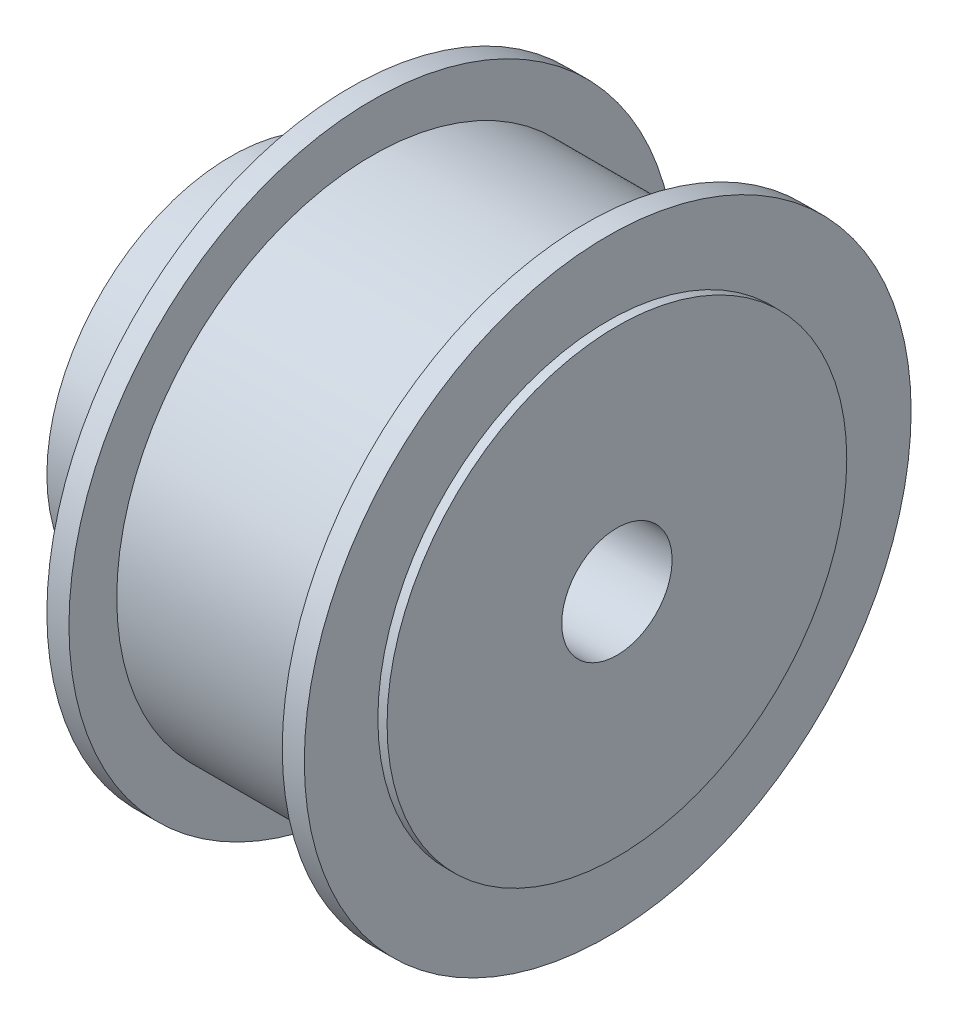
SolidWorks part; units mm, degrees
ref_plane "Alzado" through (0, 0, 0) normal (0, 0, 1) x (1, 0, 0)
ref_plane "Planta" through (0, 0, 0) normal (0, 1, 0) x (1, 0, 0)
ref_plane "Vista lateral" through (0, 0, 0) normal (1, 0, 0) x (0, 0, -1)
sketch "Croquis1" plane through (0, 0, 0) normal (1, 0, 0) x (0, 0, -1)
  circle A0 centre (0, 0) radius 10
  dimension "D1" = 20
extrude "Saliente-Extruir1" add sketch "Croquis1" along normal blind 6
sketch "Croquis2" plane through (6, 0, 0) normal (1, 0, 0) x (0, 0, -1)
  circle A0 centre (0, 0) radius 12.5
  dimension "D1" = 25
extrude "Saliente-Extruir2" add sketch "Croquis2" along normal blind 0.5
sketch "Croquis3" plane through (6.5, 0, 0) normal (1, 0, 0) x (0, 0, -1)
  circle A0 centre (0, 0) radius 16.5
  dimension "D1" = 33
extrude "Saliente-Extruir3" add sketch "Croquis3" along normal blind 1.2
sketch "Croquis4" plane through (7.7, 0, 0) normal (1, 0, 0) x (0, 0, -1)
  circle A0 centre (0, 0) radius 13.9
  dimension "D1" = 27.8
extrude "Saliente-Extruir4" add sketch "Croquis4" along normal blind 11.6
sketch "Croquis5" plane through (19.3, 0, 0) normal (1, 0, 0) x (0, 0, -1)
  circle A0 centre (0, 0) radius 16.5
  dimension "D1" = 33
extrude "Saliente-Extruir5" add sketch "Croquis5" along normal blind 1.2
sketch "Croquis6" plane through (20.5, 0, 0) normal (1, 0, 0) x (0, 0, -1)
  circle A0 centre (0, 0) radius 12.5
  dimension "D1" = 25
extrude "Saliente-Extruir6" add sketch "Croquis6" along normal blind 0.5
sketch "Croquis7" plane through (0, 0, 0) normal (-1, 0, 0) x (0, 0, 1)
  circle A0 centre (0, 0) radius 3
  dimension "D1" = 6
extrude "Cortar-Extruir1" cut sketch "Croquis7" against normal through all
ref_plane "Plano1" through (0, 0, -10) normal (0, 0, -1) x (-1, 0, 0)
sketch "Croquis8" plane through (0, 0, -10) normal (0, 0, -1) x (-1, 0, 0)
  point P4 (-3, 0)
  point P8 (-3, 0)
  dimension "D1" = 3
hole_wizard "Taladro roscado M41" positions "Croquis8" profile "Croquis10" tap size "M4" standard "ISO"
sketch "Croquis10" plane through (3, 0, -10) normal (1, 0, 0) x (0, 1, 0)
  line L0 (0, 0) -> (0, 12.4914)
  line L1 (0, 12.4914) -> (1.65, 11.5)
  line L2 (1.65, 11.5) -> (1.65, 0)
  line L5 (1.65, 0) -> (0, 0)
  line L10 (0, 12.4914) -> (-1.65, 11.5) construction
  line L11 (0, -6.35) -> (0, 107.95) construction
  dimension "Diámetro de perforador para roscar" = 3.3
  dimension "Profundidad de perforador para roscar" = 11.5
  dimension "Ángulo de perforador" = 118
cosmetic thread "Rosca de taladro4" parameters "D1"=8, "D2"=4
